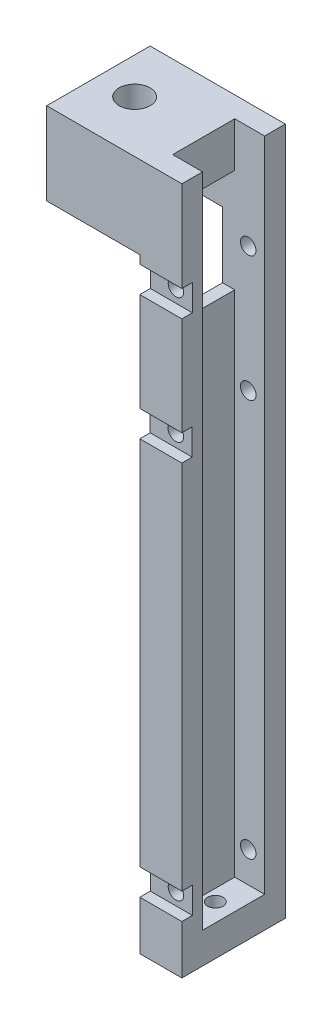
SolidWorks part; units mm, degrees
material "Delrin 2700 NC010, Low Viscosity Acetal Copolymer (SS)"
ref_plane "Front Plane" through (0, 0, 0) normal (0, 0, 1) x (1, 0, 0)
ref_plane "Top Plane" through (0, 0, 0) normal (0, 1, 0) x (1, 0, 0)
ref_plane "Right Plane" through (0, 0, 0) normal (1, 0, 0) x (0, 0, -1)
sketch "Sketch1" plane through (0, 0, 0) normal (0, 0, 1) x (1, 0, 0)
  line L0 (-4, 0) -> (-0.82, 0)
  line L1 (-0.82, 0) -> (-0.82, 21.5)
  line L2 (-6.32, 21.5) -> (-6.32, 17.5)
  line L3 (-4, 17.5) -> (-4, 0)
  line L4 (-6.32, 17.5) -> (-4, 17.5)
  line L5 (-0.82, 21.5) -> (-6.32, 21.5)
  dimension "D1" = 3.18
  dimension "D2" = 5.5
  dimension "D3" = 4
extrude "Boss-Extrude2" add sketch "Sketch1" along normal blind 10
sketch "Sketch2" plane through (-0.82, 0, 0) normal (1, 0, 0) x (0, 0, -1)
  line L1 (-10, 0) -> (0, 0) construction
  line L3 (-8, 0) -> (-2, 0)
  line L4 (-2, 0) -> (-2, 21.5)
  line L5 (-10, 21.5) -> (0, 21.5) construction
  line L6 (-2, 21.5) -> (-8, 21.5)
  line L7 (-8, 21.5) -> (-8, 0)
extrude "Cut-Extrude1" cut sketch "Sketch2" against normal blind 2
sketch "Sketch18" plane through (-6.32, 0, 0) normal (-1, 0, 0) x (0, 0, 1)
  line L0 (0, 21.5) -> (0, 17.5)
  line L1 (0, 21.5) -> (10, 21.5)
  line L2 (10, 21.5) -> (10, 17.5)
  line L3 (10, 17.5) -> (0, 17.5)
extrude "Cut-Extrude6" cut sketch "Sketch18" against normal blind 2.32
sketch "Sketch19" plane through (0, 21.5, 0) normal (0, 1, 0) x (1, 0, 0)
  line L0 (-0.82, -10) -> (-4, -10)
  line L1 (-4, -10) -> (-4, 0)
  line L2 (-4, 0) -> (-0.82, 0)
  line L3 (-0.82, 0) -> (-0.82, -2)
  line L4 (-0.82, -2) -> (-2.82, -2)
  line L5 (-2.82, -2) -> (-2.82, -8)
  line L6 (-2.82, -8) -> (-0.82, -8)
  line L7 (-0.82, -8) -> (-0.82, -10)
extrude "Boss-Extrude4" add sketch "Sketch19" along normal blind 35.965
sketch "Sketch20" plane through (-4, 0, 0) normal (-1, 0, 0) x (0, 0, 1)
  line L0 (10, 57.465) -> (10, 53.147)
  line L1 (10, 57.465) -> (10, 0) construction
  line L2 (10, 53.147) -> (0, 53.147)
  line L3 (0, 57.465) -> (0, 0) construction
  line L4 (0, 53.147) -> (0, 57.465)
  line L5 (0, 57.465) -> (10, 57.465)
  dimension "D1" = 4.318
extrude "Boss-Extrude5" add sketch "Sketch20" along normal blind 9
ref_plane "Plane1" through (0, 0, 5) normal (0, 0, 1) x (1, 0, 0)
sketch "Sketch21" plane through (-0.82, 0, 0) normal (1, 0, 0) x (0, 0, -1)
  line L0 (-10, 0) -> (-8, 0)
  line L1 (-8, 0) -> (-8, 57.465)
  line L2 (-8, 57.465) -> (-10, 57.465)
  line L3 (-10, 57.465) -> (-10, 0)
  line L4 (-2, 0) -> (0, 0)
  line L5 (0, 0) -> (0, 57.465)
  line L6 (0, 57.465) -> (-2, 57.465)
  line L7 (-2, 57.465) -> (-2, 0)
extrude "Boss-Extrude6" add sketch "Sketch21" along normal blind 0.889
sketch "Sketch22" plane through (0, 0, 0) normal (0, -1, 0) x (1, 0, 0)
  line L0 (-4, 10) -> (0.069, 10)
  line L1 (0.069, 10) -> (0.069, 8)
  line L2 (0.069, 8) -> (-2.82, 8)
  line L3 (-2.82, 8) -> (-2.82, 2)
  line L4 (-2.82, 2) -> (0.069, 2)
  line L5 (0.069, 2) -> (0.069, 0)
  line L6 (0.069, 0) -> (-4, 0)
  line L7 (-4, 0) -> (-4, 10)
extrude "Boss-Extrude7" add sketch "Sketch22" along normal blind 9.02
sketch "Sketch23" plane through (0, 0, 10) normal (0, 0, 1) x (1, 0, 0)
  line L0 (0.069, -3.02) -> (0.069, -4.29)
  line L1 (0.069, -1.75) -> (-4, -1.75)
  line L2 (0.069, 57.465) -> (0.069, -9.02) construction
  line L3 (0.069, -3.02) -> (0.069, -1.75)
  line L4 (0.069, -3.02) -> (0.069, -9.02) construction
  line L5 (-4, 53.147) -> (-4, -9.02) construction
  line L6 (-4, -1.75) -> (-4, -4.29)
  line L7 (-4, -4.29) -> (0.069, -4.29)
  line L8 (-4, 47.4267) -> (-4, 48.6967)
  line L9 (-4, 47.4267) -> (-4, 46.1567)
  line L10 (-4, 48.6967) -> (0.069, 48.6967)
  line L11 (0.069, 48.6967) -> (0.069, 46.1567)
  line L12 (0.069, 46.1567) -> (-4, 46.1567)
  dimension "D1" = 1.27
  dimension "D2" = 1.27
  dimension "D3" = 1.27
  dimension "D4" = 1.27
  dimension "D5" = 6
extrude "Cut-Extrude7" cut sketch "Sketch23" against normal blind 1.016
sketch "Sketch24" plane through (0, 0, 10) normal (0, 0, 1) x (1, 0, 0)
  line L0 (0.069, 34.085) -> (0.069, 36.625)
  line L1 (0.069, 46.1567) -> (0.069, -1.75) construction
  line L2 (-4, 46.1567) -> (-4, -1.75) construction
  line L5 (0.069, 36.625) -> (-4, 36.625)
  line L6 (-4, 36.625) -> (-4, 34.085)
  line L7 (-4, 34.085) -> (0.069, 34.085)
extrude "Cut-Extrude8" cut sketch "Sketch24" against normal blind 1
extrude "Cut-Extrude9" cut sketch "Sketch25" against normal through all
sketch "Sketch25" plane through (35.0631, -23.6783, 8.984) normal (0, 0, 1) x (1, 0, 0)
  circle A0 centre (-36.5816, 71.105) radius 0.7556
  circle A1 centre (-36.5816, 59.0333) radius 0.7556
  circle A2 centre (-36.5816, 25.3583) radius 0.7557
extrude "Cut-Extrude14" cut sketch "Sketch30" against normal through all
sketch "Sketch30" plane through (35.0631, -23.6783, 9) normal (0, 0, 1) x (1, 0, 0)
  circle A0 centre (-36.5816, 59.0333) radius 0.7556
sketch "Sketch34" plane through (0, 57.465, 0) normal (0, 1, 0) x (1, 0, 0)
  line L2 (-2.3749, -5) -> (2.3749, -5) construction
  circle A0 centre (-9.5, -5) radius 1.5
  dimension "D1" = 3
extrude "Cut-Extrude18" cut sketch "Sketch34" against normal blind 10
sketch "Sketch35" plane through (0, 0, 8.984) normal (0, 0, 1) x (1, 0, 0)
  line L0 (-1.5185, 35.355) -> (-1.5185, 46.1567) construction
  line L1 (-4, 46.1567) -> (0.069, 46.1567) construction
  line L2 (-1.5185, 35.355) -> (-1.5185, -1.75) construction
  line L3 (0.069, -1.75) -> (-4, -1.75) construction
  line L4 (-1.5185, 46.1567) -> (-1.5185, 47.4567) construction
  line L5 (-1.5185, -1.75) -> (-1.5185, -3.05) construction
  circle A0 centre (-1.5185, 47.4567) radius 0.75
  circle A1 centre (-1.5185, -3.05) radius 0.75
  dimension "D2" = 1.3
  dimension "D1" = 1.3
extrude "Cut-Extrude19" cut sketch "Sketch35" against normal through all
sketch "Sketch36" plane through (-2.82, 0, 0) normal (1, 0, 0) x (0, 0, -1)
  line L0 (-8, 53.147) -> (-2, 53.147) construction
  line L1 (-8, 57.465) -> (-8, -9.02) construction
  line L2 (0, 53.147) -> (-10, 53.147) construction
  line L3 (-2, 57.465) -> (-2, -9.02) construction
  line L4 (-2, -9.02) -> (-2, 57.465) construction
  line L5 (-8, 53.147) -> (-8, 43.147) construction
  line L6 (-8, -9.02) -> (-8, 57.465) construction
  line L7 (-8, 53.147) -> (-2, 53.147)
  line L8 (-8, 53.147) -> (-8, 43.147)
  line L9 (-8, 43.147) -> (-2, 43.147)
  line L10 (-2, 43.147) -> (-2, 53.147)
  dimension "D1" = 10
extrude "Cut-Extrude20" cut sketch "Sketch36" against normal blind 10
sketch "Sketch37" plane through (0, 53.147, 0) normal (0, -1, 0) x (1, 0, 0)
  line L0 (-13, 10) -> (-4, 10)
  line L1 (-4, 10) -> (-4, 8)
  line L2 (-4, 8) -> (-13, 8)
  line L3 (-13, 0) -> (-13, 10) construction
  line L4 (-13, 8) -> (-13, 10)
  line L5 (-4, 2) -> (-4, 0)
  line L6 (-4, 0) -> (-13, 0)
  line L7 (-4, 2) -> (-13, 2)
  line L8 (-13, 2) -> (-13, 0)
extrude "Boss-Extrude8" add sketch "Sketch37" along normal blind 3.65
sketch "Sketch38" plane through (0, -9.02, 0) normal (0, -1, 0) x (1, 0, 0)
  line L0 (-4, 10) -> (0.069, 10)
  line L1 (0.069, 10) -> (0.069, 0)
  line L2 (0.069, 0) -> (-4, 0)
  line L3 (-4, 0) -> (-4, 10)
extrude "Boss-Extrude9" add sketch "Sketch38" against normal blind 3
sketch "Sketch39" plane through (0, -9.02, 0) normal (0, -1, 0) x (1, 0, 0)
  line L0 (-4, 10) -> (-1.7, 10) construction
  line L4 (0.069, 10) -> (-4, 10) construction
  line L6 (-1.7, 10) -> (-1.7, 0) construction
  line L7 (-4, 0) -> (0.069, 0) construction
  circle A0 centre (-1.7, 5) radius 0.75
  dimension "D2" = 1.5
  dimension "D1" = 2.3
extrude "Cut-Extrude21" cut sketch "Sketch39" against normal blind 3
